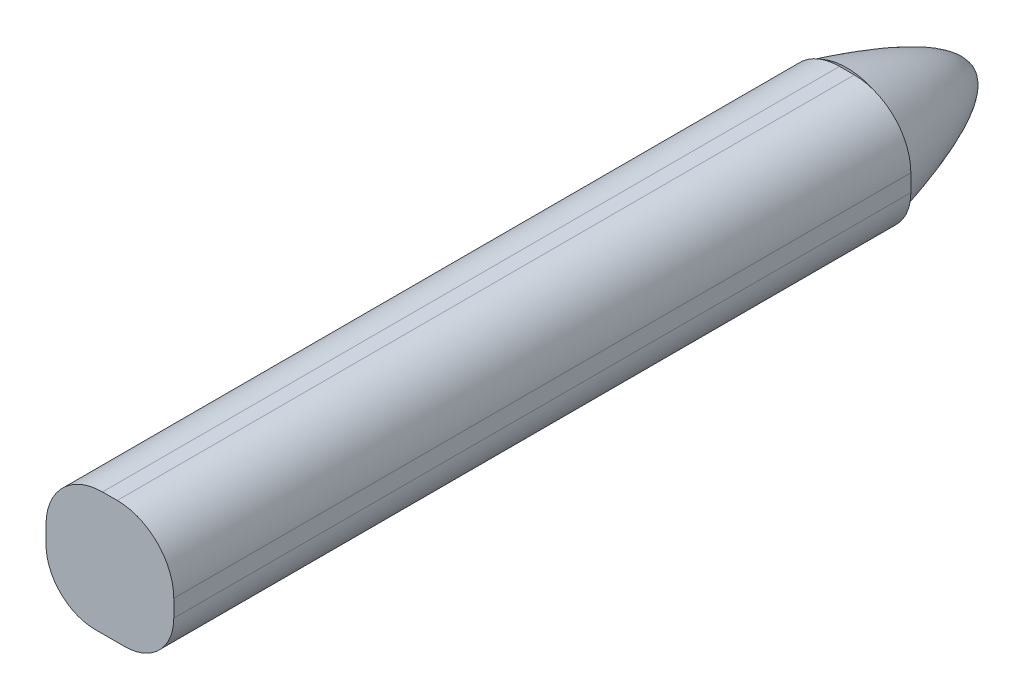
SolidWorks part; units mm, degrees
ref_plane "Front Plane" through (0, 0, 0) normal (0, 0, 1) x (1, 0, 0)
ref_plane "Top Plane" through (0, 0, 0) normal (0, 1, 0) x (1, 0, 0)
ref_plane "Right Plane" through (0, 0, 0) normal (1, 0, 0) x (0, 0, -1)
sketch "Sketch1" plane through (0, 0, 0) normal (0, 0, 1) x (1, 0, 0)
  line L0 (0, 0) -> (0, -1250) construction
  line L1 (0, 0) -> (0, 1250) construction
  line L2 (0, 0) -> (1300, 0) construction
  line L3 (0, 0) -> (-1300, 0) construction
  line L5 (-300, -1250) -> (300, -1250)
  line L6 (-1300, -250) -> (-1300, 100)
  line L7 (-150, 1250) -> (150, 1250)
  line L8 (1300, -250) -> (1300, 100)
  arc A0 (1300, -250) -> (300, -1250) centre (300, -250) cw
  arc A1 (-300, -1250) -> (-1300, -250) centre (-300, -250) cw
  arc A2 (150, 1250) -> (1300, 100) centre (150, 100) cw
  arc A3 (-150, 1250) -> (-1300, 100) centre (-150, 100) ccw
  dimension "D1" = 1000
  dimension "D2" = 1150
extrude "Boss-Extrude1" add sketch "Sketch1" along normal mid plane 15000
sketch "Sketch2" plane through (0, 0, 0) normal (0, 1, 0) x (1, 0, 0)
  line L0 (0, 7500) -> (-1300, 7500)
  line L1 (150, 7500) -> (-150, 7500) construction
  line L2 (-1300, -7500) -> (-1300, 7500) construction
  line L3 (-150, 7500) -> (-1300, 7500) construction
  line L4 (0, 7500) -> (0, 10000)
  spline S0 degree 2 poles (-1300, 7500) (-650, 10000) (0, 10000) knots 0 0 0 0.5 0.5 0.5
revolve "Revolve1" add sketch "Sketch2" angle 360 about L4
